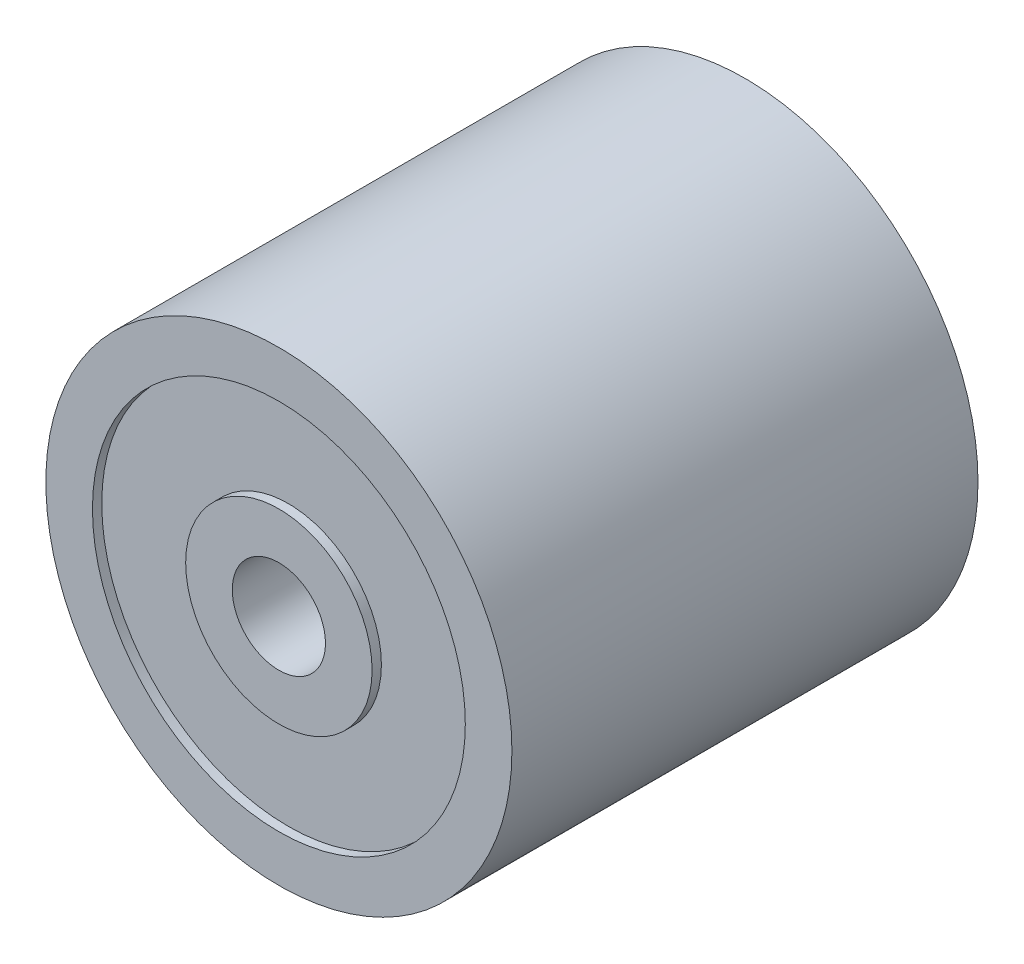
SolidWorks part; units mm, degrees
ref_plane "Front Plane" through (0, 0, 0) normal (0, 0, 1) x (1, 0, 0)
ref_plane "Top Plane" through (0, 0, 0) normal (0, 1, 0) x (1, 0, 0)
ref_plane "Right Plane" through (0, 0, 0) normal (1, 0, 0) x (0, 0, -1)
sketch "Sketch1" plane through (0, 0, 0) normal (0, 0, 1) x (1, 0, 0)
  circle A2 centre (0, 0) radius 1.27
  circle A3 centre (0, 0) radius 6.35
  dimension "D1" = 2.54
  dimension "D2" = 12.7
extrude "Boss-Extrude1" add sketch "Sketch1" along normal blind 12.7
sketch "Sketch2" plane through (0, 0, 12.7) normal (0, 0, 1) x (1, 0, 0)
  circle A0 centre (0, 0) radius 1.27 construction
  circle A1 centre (0, 0) radius 1.27
  circle A2 centre (0, 0) radius 5.08
  circle A3 centre (0, 0) radius 2.54
  dimension "D1" = 10.16
  dimension "D2" = 5.08
extrude "Cut-Extrude1" cut sketch "Sketch2" against normal blind 0.254 contours A2 A3
ref_plane "Plane1" through (0, 0, 6.35) normal (0, 0, 1) x (1, 0, 0)
mirror "Mirror1" about plane through (0, 0, 6.35) normal (0, 0, 1) of "Cut-Extrude1"
equation "\"Shaftdia\"=0.1"
equation "\"D1@Sketch1\"=\"Shaftdia\""
equation "\"D2@Sketch1\"=\"Shaftdia\"+0.4in"
equation "\"D1@Sketch2\"=\"Shaftdia\"+0.3in"
equation "\"D2@Sketch2\"=\"Shaftdia\"+0.1"
